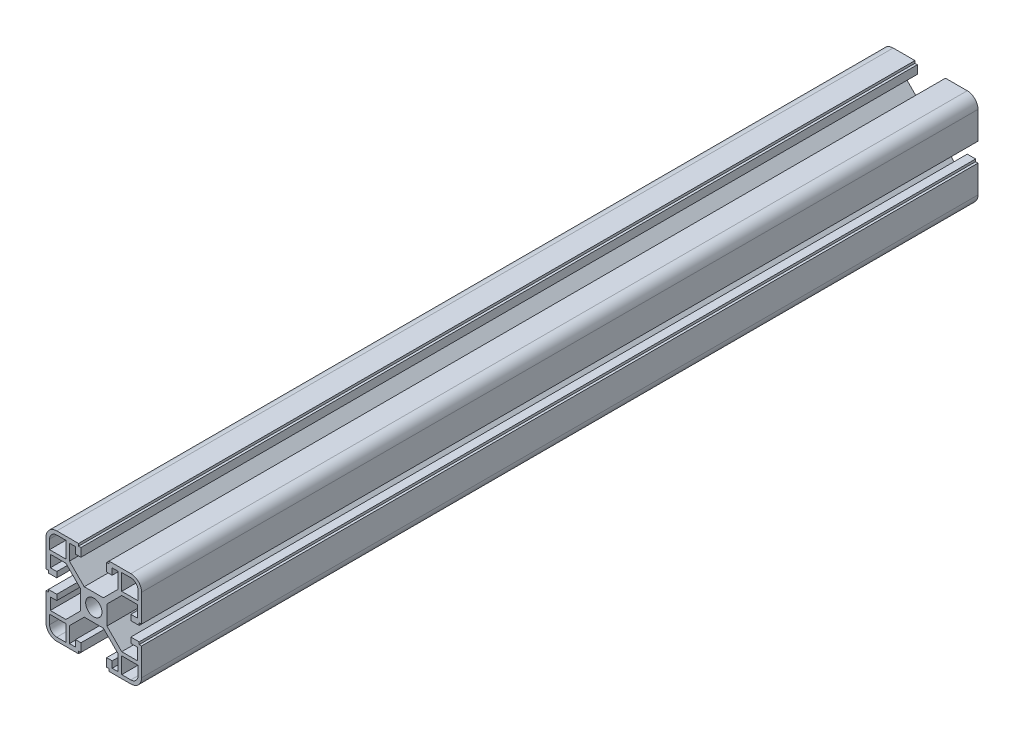
SolidWorks part; units mm, degrees
material "6061-T6 (SS)"
ref_plane "Front Plane" through (0, 0, 0) normal (0, 0, 1) x (1, 0, 0)
ref_plane "Top Plane" through (0, 0, 0) normal (0, 1, 0) x (1, 0, 0)
ref_plane "Right Plane" through (0, 0, 0) normal (1, 0, 0) x (0, 0, -1)
sketch "Sketch1" plane through (0, 0, 0) normal (0, 0, 1) x (1, 0, 0)
  line L0 (3.4, 0) -> (5.5, 0)
  line L1 (10.19, 11.69) -> (4, 5.5)
  line L2 (11.69, 10.19) -> (5.5, 4)
  line L3 (18.2, 10.19) -> (11.69, 10.19)
  line L4 (18.2, 10.19) -> (18.2, 5.2656)
  line L5 (18.2, 5.2656) -> (15.5, 5.2656)
  line L6 (15.5, 5.2656) -> (15.5, 2.9656)
  line L7 (15.5, 2.9656) -> (19, 2.9656)
  line L8 (19, 2.9656) -> (19, 3.9656)
  line L9 (19, 3.9656) -> (20, 3.9656)
  line L10 (20, 3.9656) -> (20, 15.5)
  line L11 (15.5, 20) -> (6.3853, 20)
  line L12 (18.5, 11.69) -> (18.5, 15.5)
  line L13 (15.5, 18.5) -> (11.69, 18.5)
  line L14 (11.69, 11.69) -> (11.69, 18.5)
  line L15 (0, 3.4) -> (0, 5.5)
  line L16 (4, 5.5) -> (0, 5.5)
  line L17 (6.3853, 20) -> (6.3853, 19)
  line L18 (5.5, 0) -> (5.5, 4)
  line L19 (6.3853, 19) -> (5.3853, 19)
  line L20 (5.3853, 19) -> (5.3853, 15.5)
  line L21 (5.3853, 15.5) -> (7.6853, 15.5)
  line L22 (10.19, 11.69) -> (10.19, 18.2)
  line L23 (11.69, 11.69) -> (18.5, 11.69)
  line L24 (7.6853, 18.2) -> (7.6853, 15.5)
  line L25 (10.19, 18.2) -> (7.6853, 18.2)
  arc A0 (20, 15.5) -> (15.5, 20) centre (15.5, 15.5) ccw
  arc A1 (18.5, 15.5) -> (15.5, 18.5) centre (15.5, 15.5) ccw
  arc A2 (3.4, 0) -> (0, 3.4) centre (0, 0) ccw
  dimension "D3" = 4.5
  dimension "D18" = 1.5
  dimension "D9" = 3.4
  dimension "D20" = 1.8
  dimension "D25" = 3
  dimension "D1" = 5.5
  dimension "D2" = 1.5
  dimension "D4" = 14.5
  dimension "D5" = 1.5
  dimension "D6" = 2.1
  dimension "D7" = 2.3
  dimension "D8" = 1.8
  dimension "D10" = 6.81
  dimension "D11" = 2.1
  dimension "D12" = 1
  dimension "D13" = 4.5
  dimension "D14" = 45
  dimension "D15" = 14.5
  dimension "D16" = 1
  dimension "D17" = 1.5
  dimension "D19" = 6.81
  dimension "D21" = 4.5
  dimension "D22" = 2.3
  dimension "D23" = 1
  dimension "D24" = 1
  dimension "D26" = 8.754
  dimension "D27" = 8.754
  dimension "D28" = 4.9244
  dimension "D29" = 2.5047
extrude "Boss-Extrude1" add sketch "Sketch1" along normal blind 350
mirror "Mirror1" about plane through (0, 0, 0) normal (0, 1, 0) of "Boss-Extrude1"
mirror "Mirror2" about plane through (0, 0, 0) normal (1, 0, 0) of "Boss-Extrude1"
mirror "Mirror3" about plane through (0, 0, 0) normal (0, 1, 0) of "Mirror2"
